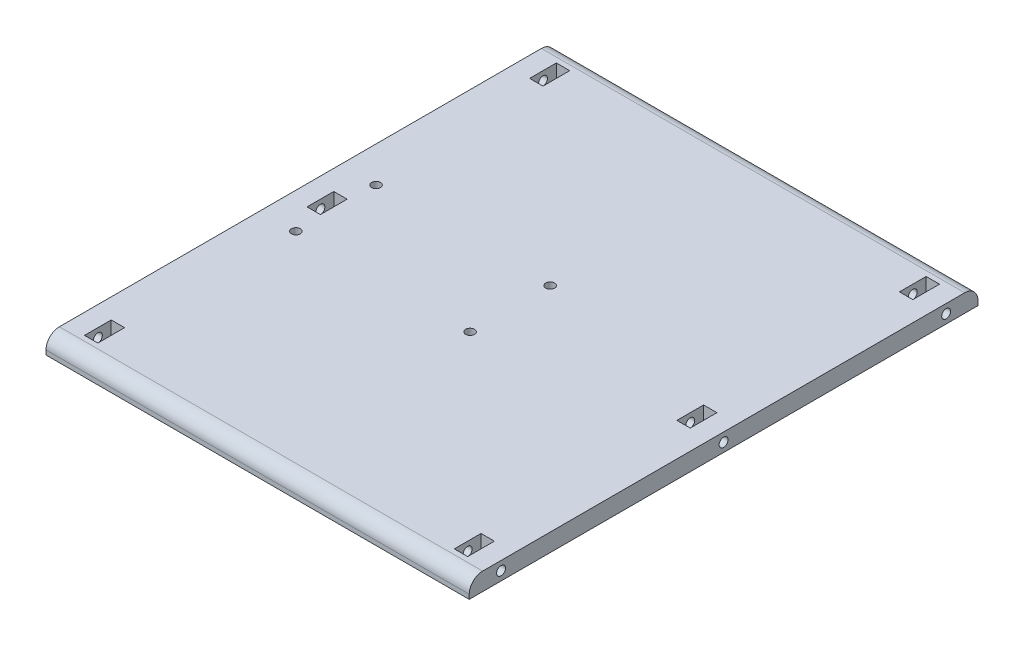
SolidWorks part; units mm, degrees
ref_plane "Plan de face" through (0, 0, 0) normal (0, 0, 1) x (1, 0, 0)
ref_plane "Plan de dessus" through (0, 0, 0) normal (0, 1, 0) x (1, 0, 0)
ref_plane "Plan de droite" through (0, 0, 0) normal (1, 0, 0) x (0, 0, -1)
sketch "Esquisse1" plane through (0, 0, 0) normal (0, 1, 0) x (1, 0, 0)
  line L0 (41.54, -57.15) -> (41.54, 57.15) construction
  line L1 (-47.54, 57.15) -> (47.54, 57.15)
  line L2 (-47.54, 57.15) -> (-47.54, -57.15)
  line L3 (-47.54, -57.15) -> (47.54, -57.15)
  line L4 (47.54, 57.15) -> (47.54, -57.15)
  line L5 (-47.54, 57.15) -> (47.54, -57.15) construction
  line L6 (-47.54, -57.15) -> (47.54, 57.15) construction
  line L7 (-41.54, -57.15) -> (-41.54, 57.15) construction
  line L8 (40.04, -3) -> (40.04, 3)
  line L9 (43.04, -53) -> (40.04, -53)
  line L10 (43.04, -53) -> (43.04, -47)
  line L11 (43.04, -47) -> (40.04, -47)
  line L12 (40.04, -53) -> (40.04, -47)
  line L13 (43.04, -53) -> (40.04, -47) construction
  line L14 (43.04, -47) -> (40.04, -53) construction
  line L15 (43.04, -3) -> (40.04, -3)
  line L16 (43.04, -3) -> (43.04, 3)
  line L17 (43.04, 3) -> (40.04, 3)
  line L18 (40.04, 47) -> (40.04, 53)
  line L19 (43.04, 47) -> (40.04, 47)
  line L20 (43.04, 47) -> (43.04, 53)
  line L21 (43.04, 53) -> (40.04, 53)
  line L22 (0, -57.15) -> (0, 57.15) construction
  line L23 (-43.04, -47) -> (-40.04, -47)
  line L24 (-43.04, -53) -> (-43.04, -47)
  line L25 (-43.04, -53) -> (-40.04, -53)
  line L26 (-40.04, -53) -> (-40.04, -47)
  line L27 (-43.04, 47) -> (-40.04, 47)
  line L28 (-43.04, 47) -> (-43.04, 53)
  line L29 (-43.04, 53) -> (-40.04, 53)
  line L30 (-40.04, 47) -> (-40.04, 53)
  line L31 (-40.04, -3) -> (-40.04, 3)
  line L32 (-43.04, 3) -> (-40.04, 3)
  line L33 (-43.04, -3) -> (-43.04, 3)
  line L34 (-43.04, -3) -> (-40.04, -3)
  line L35 (-39.54, -57.15) -> (-39.54, 57.15) construction
  line L36 (-47.54, 9) -> (47.54, 9) construction
  line L37 (-47.54, -9) -> (47.54, -9) construction
  line L38 (-47.54, 0) -> (47.54, 0) construction
  circle A0 centre (-39.54, -9) radius 1
  circle A1 centre (-0.42, -9) radius 1
  circle A2 centre (-0.42, 9) radius 1
  circle A3 centre (-39.54, 9) radius 1
  point P0 (0, 0)
  point P10 (41.54, -50)
  point P11 (41.54, -50)
  dimension "D9" = 8
  dimension "D10" = 2
  dimension "D1" = 95.08
  dimension "D2" = 114.3
  dimension "D3" = 6
  dimension "D4" = 9
  dimension "D5" = 7.15
  dimension "D6" = 6
  dimension "D7" = 3
  dimension "D11" = 39.12
  dimension "D8" = 3
extrude "Boss.-Extru.1" add sketch "Esquisse1" along normal blind 4
sketch "Esquisse2" plane through (-47.54, 0, 0) normal (-1, 0, 0) x (0, 0, 1)
  line L0 (-57.15, 2) -> (57.15, 2) construction
  line L1 (-57.15, 4) -> (-57.15, 0) construction
  line L2 (57.15, 4) -> (57.15, 0) construction
  circle A0 centre (-50, 2) radius 1
  circle A1 centre (0, 2) radius 1
  circle A2 centre (50, 2) radius 1
  dimension "D1" = 7.15
  dimension "D2" = 3
extrude "Enlèv. mat.-Extru.1" cut sketch "Esquisse2" against normal blind 10
sketch "Esquisse3" plane through (47.54, 0, 0) normal (1, 0, 0) x (0, 0, -1)
  line L0 (-57.15, 2) -> (57.15, 2) construction
  line L1 (-57.15, 4) -> (-57.15, 0) construction
  line L2 (57.15, 4) -> (57.15, 0) construction
  circle A0 centre (-50, 2) radius 1
  circle A1 centre (0, 2) radius 1
  circle A2 centre (50, 2) radius 1
  dimension "D1" = 7.15
  dimension "D2" = 3
extrude "Enlèv. mat.-Extru.2" cut sketch "Esquisse3" against normal blind 10
fillet "Congé1" radius 3 2 edges at (0, 4, -57.15) (0, 4, 57.15)
